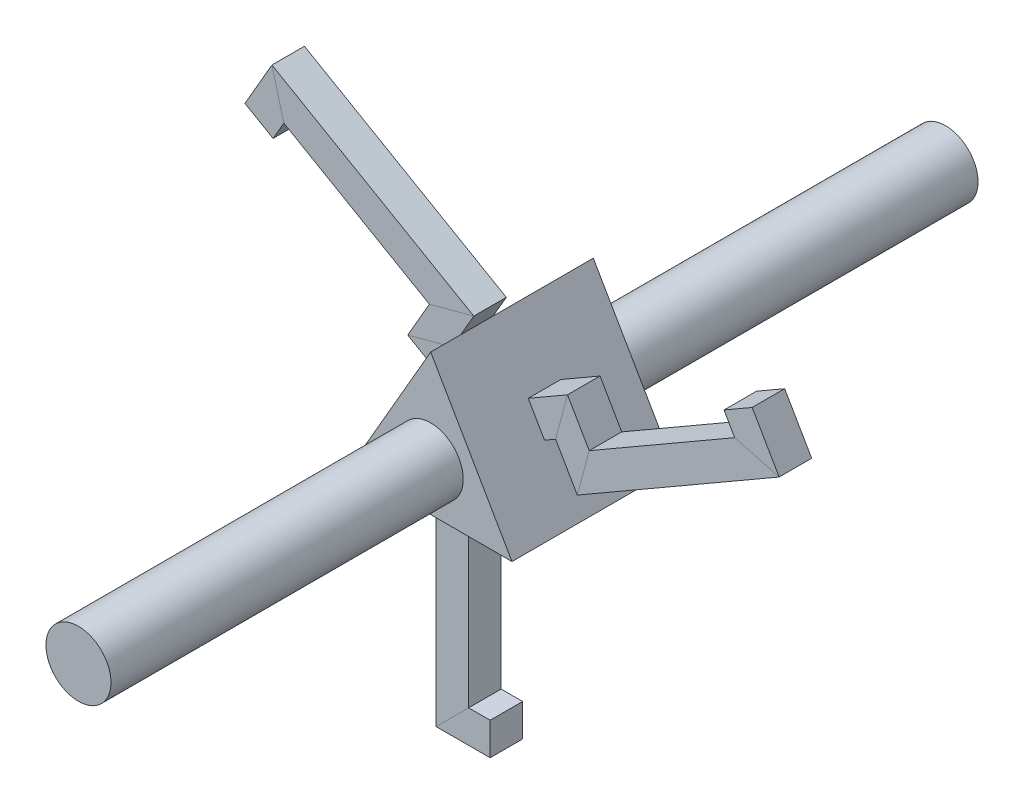
SolidWorks part; units mm, degrees
ref_plane "Plan de face" through (0, 0, 0) normal (0, 0, 1) x (1, 0, 0)
ref_plane "Plan de dessus" through (0, 0, 0) normal (0, 1, 0) x (1, 0, 0)
ref_plane "Plan de droite" through (0, 0, 0) normal (1, 0, 0) x (0, 0, -1)
sketch "Esquisse1" plane through (0, 0, 0) normal (0, 0, 1) x (1, 0, 0)
  line L0 (-20.3654, 6.1489) -> (-57.8654, -58.803)
  line L1 (-57.8654, -58.803) -> (17.1346, -58.803)
  line L2 (17.1346, -58.803) -> (-20.3654, 6.1489)
  dimension "D1" = 75
extrude "Boss.-Extru.1" add sketch "Esquisse1" along normal blind 75
sketch "Esquisse3" plane through (0, 0, 75) normal (0, 0, 1) x (1, 0, 0)
  line L0 (-57.8654, -58.803) -> (17.1346, -58.803) construction
  line L1 (-20.3654, 6.1489) -> (-57.8654, -58.803) construction
  circle A0 centre (-20.3654, -37.1523) radius 15
  dimension "D3" = 30
  dimension "D1" = 21.6506
  dimension "D2" = 21.6506
extrude "Boss.-Extru.2" add sketch "Esquisse3" along normal blind 162.5 contours A0
sketch "Esquisse4" plane through (0, 0, 0) normal (0, 0, -1) x (-1, 0, 0)
  line L0 (-17.1346, -58.803) -> (20.3654, 6.1489) construction
  line L1 (57.8654, -58.803) -> (-17.1346, -58.803) construction
  circle A0 centre (20.3654, -37.1523) radius 15
  point P4 (1.6154, -26.327)
  dimension "D3" = 30
  dimension "D1" = 21.6506
  dimension "D2" = 21.6506
extrude "Boss.-Extru.3" add sketch "Esquisse4" along normal blind 162.5
sketch "Esquisse5" plane through (0, -58.803, 0) normal (0, -1, 0) x (1, 0, 0)
  line L0 (-35.3654, 0) -> (-5.3654, 0) construction
  line L1 (-12.8654, 30) -> (-27.8654, 30)
  line L2 (-12.8654, 30) -> (-12.8654, 45)
  line L3 (-12.8654, 45) -> (-27.8654, 45)
  line L4 (-27.8654, 30) -> (-27.8654, 45)
  line L5 (17.1346, 75) -> (17.1346, 0) construction
  point P8 (17.1346, 37.5)
  dimension "D1" = 30
  dimension "D2" = 30
  dimension "D3" = 15
sketch3d "Esquisse3D2"
  line L0 (-12.9505, -56.834, 37.5) -> (-12.9505, -79.631, 37.5)
  line L1 (-12.9505, -79.631, 37.5) -> (-32.9505, -79.631, 37.5)
  line L2 (-32.9505, -79.631, 37.5) -> (-32.9505, -157.3281, 37.5)
  line L3 (-32.9505, -157.3281, 37.5) -> (-22.9505, -157.3281, 37.5)
  dimension "D1" = 37.5
  dimension "D2" = 20
  dimension "D3" = 10
  dimension "D4" = 22.7969
  dimension "D5" = 77.6971
sweep "Balayage1" add profiles "Esquisse5" path "Esquisse3D2"
pattern_circular "Répétition circulaire2" count 3 every 120 about axis through (-20.3654, -37.1523, 0) along (0, 0, 1) of "Balayage1"
equation "\"D1@Boss.-Extru.1\"= \"D1@Esquisse1\""
equation "\"D2@Esquisse3\" = \"D1@Esquisse1\" * 3 ^ 0.5 / 6"
equation "\"D1@Esquisse4\"= \"D2@Esquisse3\""
equation "\"D2@Esquisse4\"= \"D2@Esquisse3\""
equation "\"D1@Boss.-Extru.2\"= ( 400 - \"D1@Boss.-Extru.1\" ) / 2"
equation "\"D1@Boss.-Extru.3\"= \"D1@Boss.-Extru.2\""
equation "\"D3@Esquisse4\"= 0.4 * \"D1@Esquisse1\""
equation "\"D3@Esquisse3\"= 0.4 * \"D1@Esquisse1\""
equation "\"D1@Esquisse3\"= \"D2@Esquisse3\""
equation "\"D3@Esquisse5\" = 1 / 5 * \"D1@Boss.-Extru.1\""
equation "\"D1@Esquisse5\"= 0.4 * \"D1@Esquisse1\""
equation "\"D2@Esquisse5\"= \"D1@Esquisse5\""
